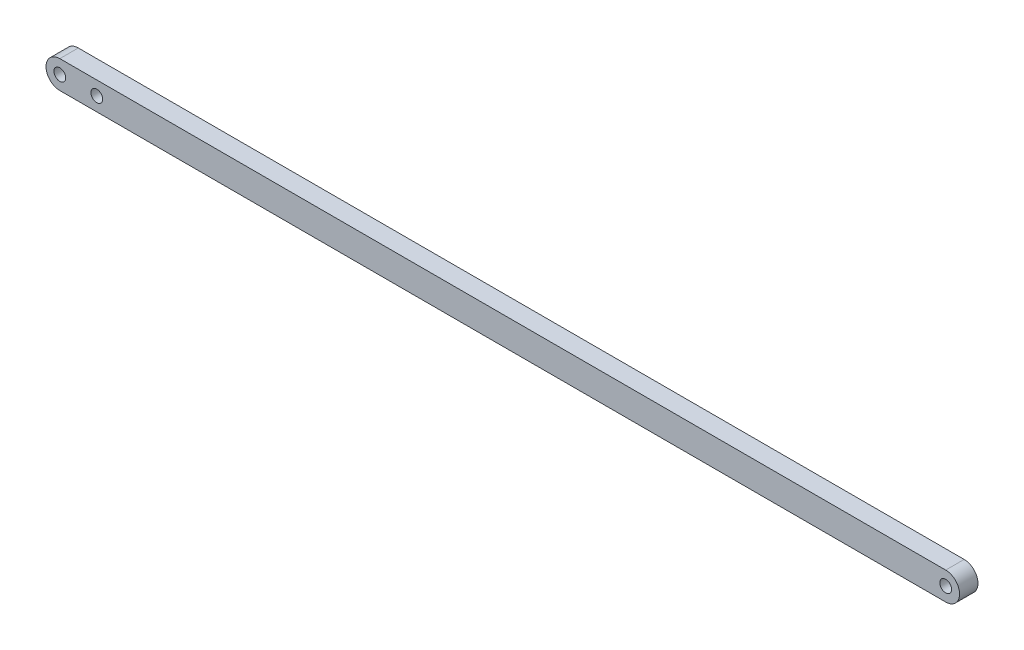
SolidWorks part; units mm, degrees
ref_plane "Front Plane" through (0, 0, 0) normal (0, 0, 1) x (1, 0, 0)
ref_plane "Top Plane" through (0, 0, 0) normal (0, 1, 0) x (1, 0, 0)
ref_plane "Right Plane" through (0, 0, 0) normal (1, 0, 0) x (0, 0, -1)
sketch "Sketch1" plane through (0, 0, 0) normal (0, 0, 1) x (1, 0, 0)
  line L0 (0, 0) -> (304.8, 0) construction
  line L1 (0, 4.7625) -> (304.8, 4.7625)
  line L2 (0, -4.7625) -> (304.8, -4.7625)
  arc A0 (0, 4.7625) -> (0, -4.7625) centre (0, 0) ccw
  arc A1 (304.8, -4.7625) -> (304.8, 4.7625) centre (304.8, 0) ccw
  circle A2 centre (0, 0) radius 2.032
  circle A3 centre (304.8, 0) radius 2.032
  circle A4 centre (12.7, 0) radius 2.032
  point P3 (152.4, 0)
  dimension "D3" = 4.064
  dimension "D1" = 304.8
  dimension "D2" = 9.525
  dimension "D4" = 12.7
extrude "Boss-Extrude1" add sketch "Sketch1" along normal blind 6.35
